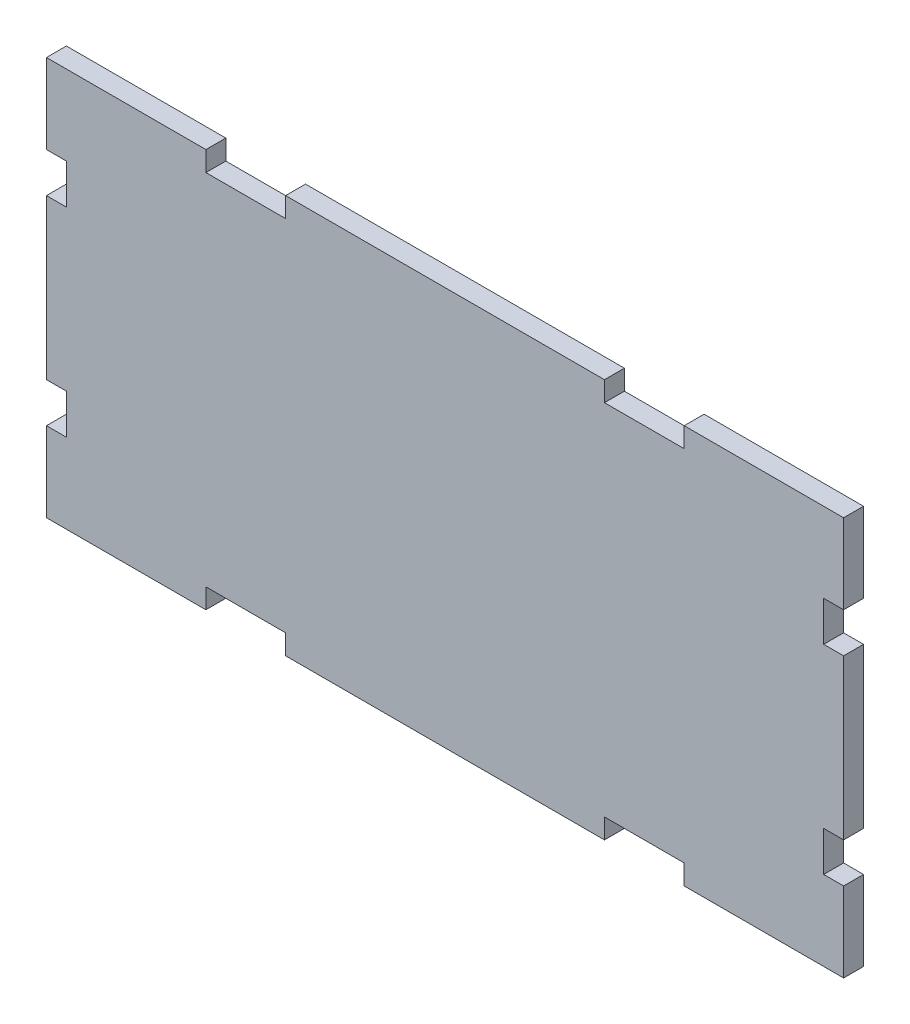
SolidWorks part; units mm, degrees
ref_plane "Front Plane" through (0, 0, 0) normal (0, 0, 1) x (1, 0, 0)
ref_plane "Top Plane" through (0, 0, 0) normal (0, 1, 0) x (1, 0, 0)
ref_plane "Right Plane" through (0, 0, 0) normal (1, 0, 0) x (0, 0, -1)
sketch "Sketch1" plane through (0, 0, 0) normal (0, 0, 1) x (1, 0, 0)
  line L0 (-105.7776, 35.818) -> (-65.7776, 35.818)
  line L1 (-65.7776, 30.818) -> (-45.7776, 30.818)
  line L2 (-100.7776, 15.818) -> (-100.7776, 5.818)
  line L3 (-65.7776, -59.182) -> (-45.7776, -59.182)
  line L4 (89.2224, 15.818) -> (89.2224, 5.818)
  line L5 (34.2224, 30.818) -> (54.2224, 30.818)
  line L6 (94.2224, 35.818) -> (94.2224, 15.818)
  line L7 (-105.7776, -64.182) -> (-65.7776, -64.182)
  line L8 (-65.7776, -59.182) -> (-65.7776, -64.182)
  line L9 (-65.7776, 30.818) -> (-65.7776, 35.818)
  line L10 (-45.7776, -64.182) -> (34.2224, -64.182)
  line L11 (-45.7776, -64.182) -> (-45.7776, -59.182)
  line L12 (-105.7776, 35.818) -> (-105.7776, 15.818)
  line L13 (34.2224, -64.182) -> (34.2224, -59.182)
  line L14 (-45.7776, 30.818) -> (-45.7776, 35.818)
  line L15 (89.2224, -34.182) -> (89.2224, -44.182)
  line L16 (54.2224, -64.182) -> (94.2224, -64.182)
  line L17 (54.2224, -59.182) -> (54.2224, -64.182)
  line L18 (-45.7776, 35.818) -> (34.2224, 35.818)
  line L19 (94.2224, 15.818) -> (89.2224, 15.818)
  line L20 (54.2224, 35.818) -> (94.2224, 35.818)
  line L28 (34.2224, -59.182) -> (54.2224, -59.182)
  line L29 (-105.7776, 15.818) -> (-100.7776, 15.818)
  line L30 (-100.7776, -34.182) -> (-100.7776, -44.182)
  line L31 (-105.7776, 5.818) -> (-100.7776, 5.818)
  line L32 (-105.7776, 5.818) -> (-105.7776, -34.182)
  line L33 (-105.7776, -34.182) -> (-100.7776, -34.182)
  line L34 (34.2224, 30.818) -> (34.2224, 35.818)
  line L35 (-105.7776, -64.182) -> (-105.7776, -44.182)
  line L36 (-105.7776, -44.182) -> (-100.7776, -44.182)
  line L38 (94.2224, 5.818) -> (89.2224, 5.818)
  line L39 (94.2224, 5.818) -> (94.2224, -34.182)
  line L40 (94.2224, -34.182) -> (89.2224, -34.182)
  line L42 (94.2224, -64.182) -> (94.2224, -44.182)
  line L43 (94.2224, -44.182) -> (89.2224, -44.182)
  line L44 (54.2224, 30.818) -> (54.2224, 35.818)
  dimension "D1" = 40
  dimension "D2" = 40
  dimension "D3" = 20
  dimension "D4" = 40
  dimension "D5" = 80
  dimension "D6" = 20
  dimension "D7" = 5
  dimension "D8" = 5
  dimension "D9" = 20
  dimension "D10" = 20
  dimension "D11" = 10
  dimension "D12" = 10
extrude "Boss-Extrude1" add sketch "Sketch1" along normal blind 5
